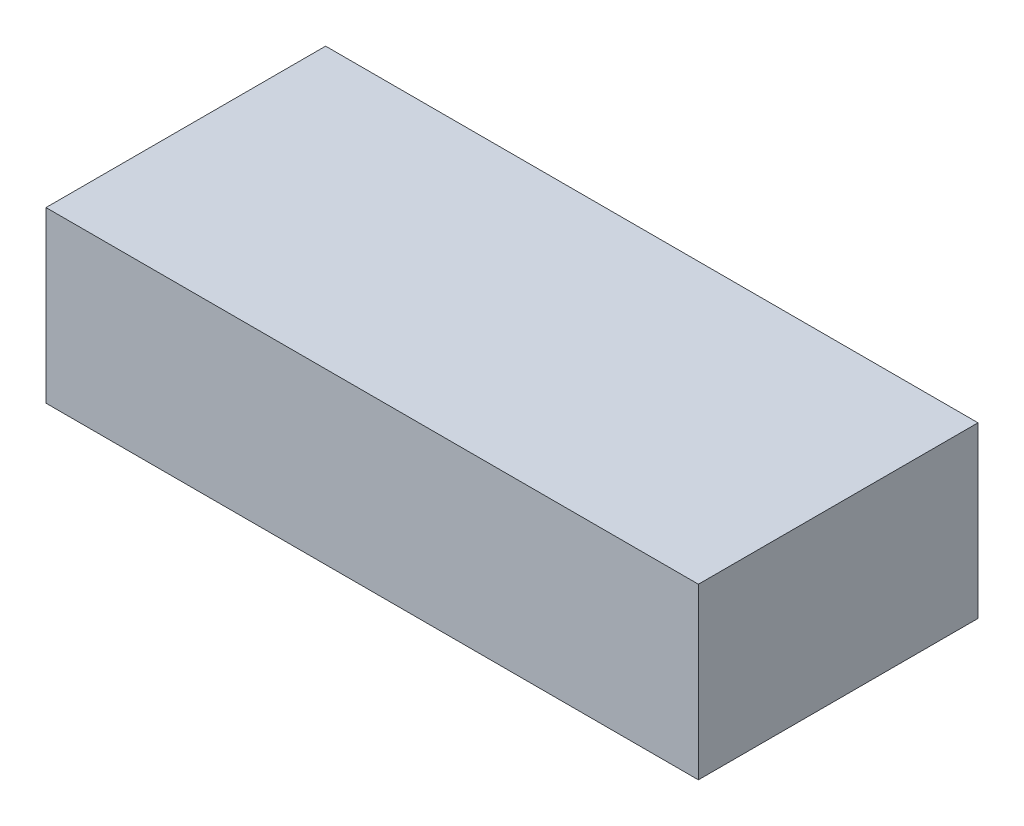
SolidWorks part; units mm, degrees
ref_plane "Front Plane" through (0, 0, 0) normal (0, 0, 1) x (1, 0, 0)
ref_plane "Top Plane" through (0, 0, 0) normal (0, 1, 0) x (1, 0, 0)
ref_plane "Right Plane" through (0, 0, 0) normal (1, 0, 0) x (0, 0, -1)
sketch "Sketch1" plane through (0, 0, 0) normal (0, 1, 0) x (1, 0, 0)
  line L1 (0, 0) -> (77, 0)
  line L2 (0, 0) -> (0, 33)
  line L3 (0, 33) -> (77, 33)
  line L4 (77, 0) -> (77, 33)
  dimension "D1" = 77
  dimension "D2" = 33
extrude "Boss-Extrude1" add sketch "Sketch1" along normal blind 20
sketch "Sketch2" plane through (0, 20, 0) normal (0, 1, 0) x (1, 0, 0)
  text T0 "Battery"
